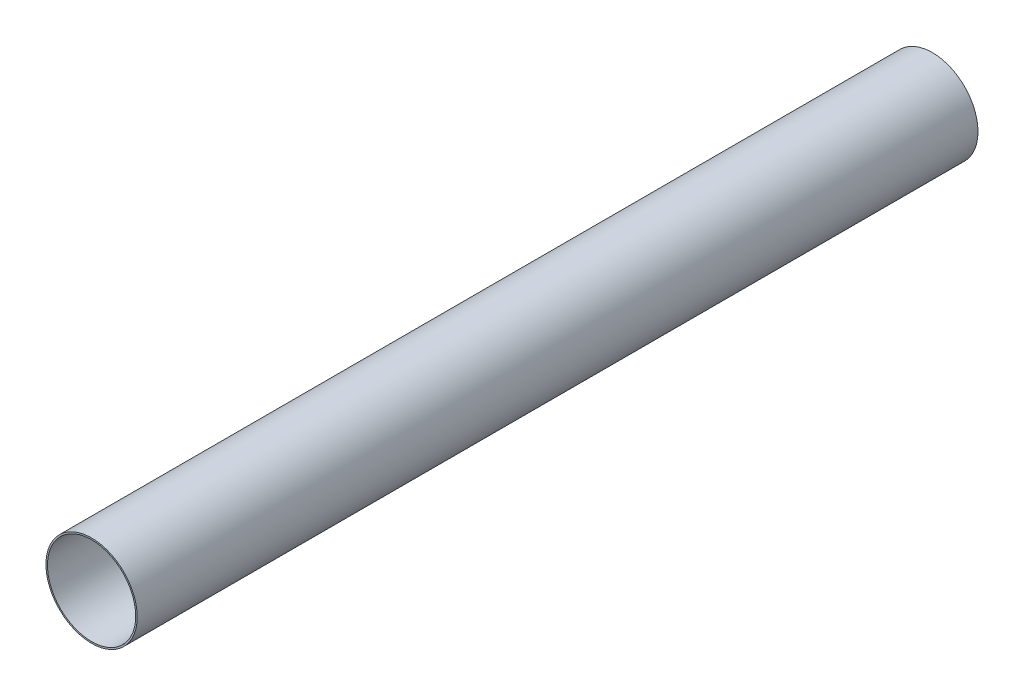
SolidWorks part; units mm, degrees
ref_plane "Front Plane" through (0, 0, 0) normal (0, 0, 1) x (1, 0, 0)
ref_plane "Top Plane" through (0, 0, 0) normal (0, 1, 0) x (1, 0, 0)
ref_plane "Right Plane" through (0, 0, 0) normal (1, 0, 0) x (0, 0, -1)
sketch "Sketch1" plane through (0, 0, 0) normal (0, 0, 1) x (1, 0, 0)
  circle A0 centre (0, 0) radius 14.6685
  circle A1 centre (0, 0) radius 15.1765
  dimension "D1" = 0.508
  dimension "D2" = 30.353
extrude "Boss-Extrude1" add sketch "Sketch1" along normal blind 279.4
